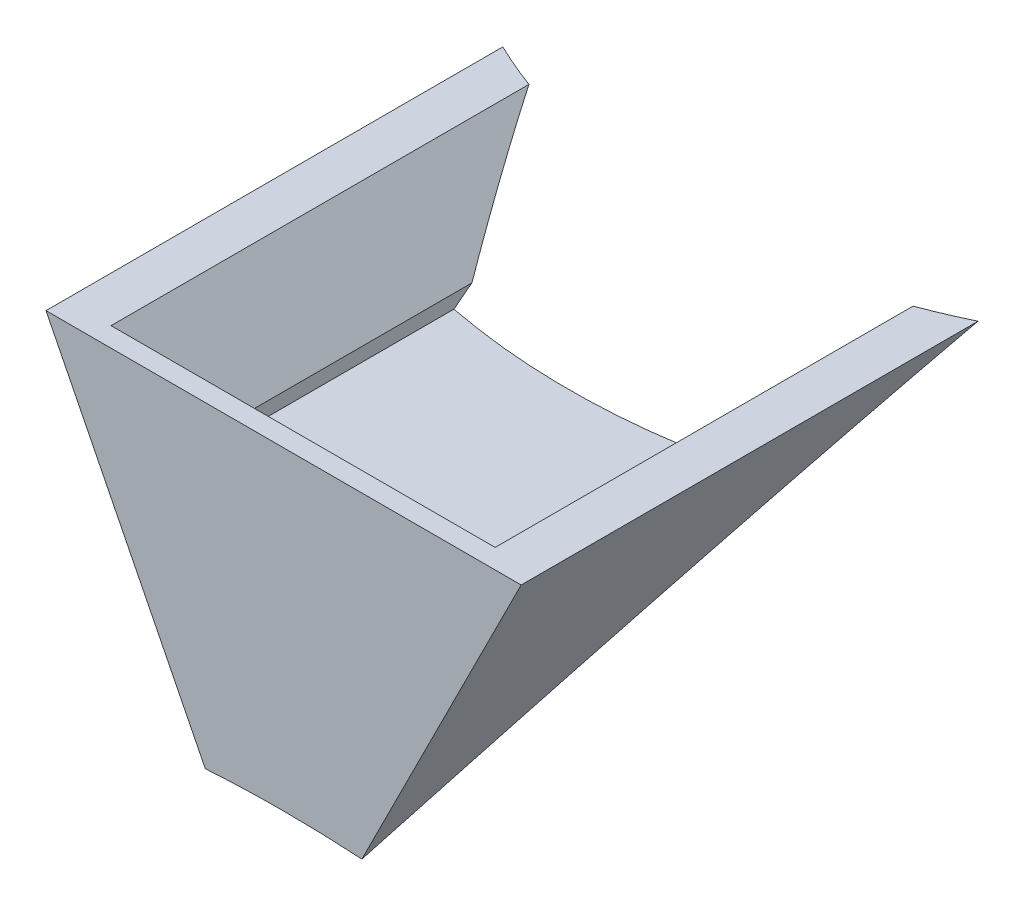
SolidWorks part; units mm, degrees
ref_plane "Plan de face" through (0, 0, 0) normal (0, 0, 1) x (1, 0, 0)
ref_plane "Plan de dessus" through (0, 0, 0) normal (0, 1, 0) x (1, 0, 0)
ref_plane "Plan de droite" through (0, 0, 0) normal (1, 0, 0) x (0, 0, -1)
sketch "Esquisse25" plane through (0, 0, 0) normal (0, 0, 1) x (1, 0, 0)
  line L1 (-19.4871, 47.0213) -> (20.5129, 47.0213)
  line L2 (20.5129, 47.0213) -> (20.5129, 49.1363)
  line L3 (20.5129, 49.1363) -> (29.5165, 61.1488)
  line L4 (29.5165, 61.1488) -> (-29.5165, 61.1488)
  line L5 (-29.5165, 61.1488) -> (-19.4871, 49.1363)
  line L6 (-19.4871, 49.1363) -> (-19.4871, 47.0213)
  line L9 (36.5165, 61.1488) -> (29.5165, 61.1488) construction
  dimension "D1" = 40
  dimension "D2" = 7
sketch "Esquisse21" plane through (0, 0, 0) normal (0, 0, 1) x (1, 0, 0)
  line L0 (0, 61.1488) -> (36.5165, 61.1488)
  line L1 (36.5165, 61.1488) -> (7.783, 3.9547)
  line L2 (7.783, 3.9547) -> (0, 3.9547)
  line L4 (0, 61.1488) -> (-36.5165, 61.1488)
  line L5 (-36.5165, 61.1488) -> (-7.783, 3.9547)
  line L6 (-7.783, 3.9547) -> (0, 3.9547)
extrude "Boss.-Extru.5" add sketch "Esquisse21" against normal blind 71.6 from offset 146
extrude "Enlèv. mat.-Extru.16" cut sketch "Esquisse25" against normal blind 68.8 from offset 143
sketch "Esquisse28" plane through (0, 0, 0) normal (0, 0, 1) x (1, 0, 0)
  line L0 (0, 80) -> (0, -62.0949)
  line L1 (0, -62.0949) -> (151.9119, -62.0949)
  line L2 (151.9119, -62.0949) -> (151.9119, 8.1801)
  line L3 (0, 80) -> (60, 80)
  line L4 (0, 178.3851) -> (0, -123.1478) construction
  line L6 (151.9119, 8.1801) -> (60, 80)
  dimension "D3" = 60
revolve "Enlèvement de matière-Révolution1" cut sketch "Esquisse28" angle 360 about L4
sketch "Esquisse29" plane through (0, 0, 0) normal (1, 0, 0) x (0, 0, -1)
  line L0 (-140.8093, 42.6783) -> (-140.8093, 21.4775)
  line L1 (-140.8093, 21.4775) -> (-113.0389, 42.6783)
  line L2 (-113.0389, 42.6783) -> (-140.8093, 42.6783)
  point P2 (-141.4216, 48.9948)
  point P4 (-140.8093, 21.4775)
  point P5 (-103.3485, 48.3297)
  point P6 (-113.0389, 42.6783)
extrude "Enlèv. mat.-Extru.17" cut sketch "Esquisse29" against normal mid plane 25.5
